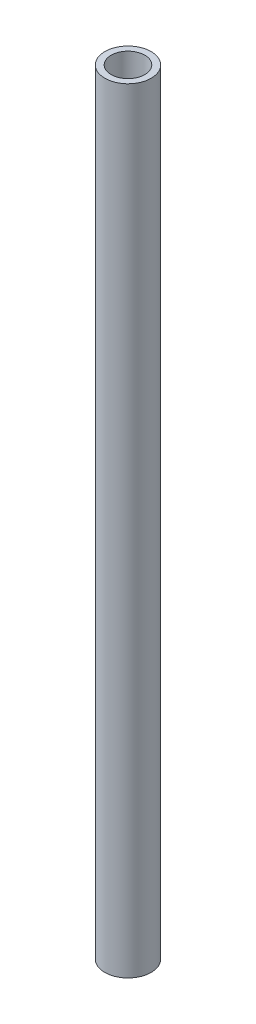
SolidWorks part; units mm, degrees
ref_plane "Front Plane" through (0, 0, 0) normal (0, 0, 1) x (1, 0, 0)
ref_plane "Top Plane" through (0, 0, 0) normal (0, 1, 0) x (1, 0, 0)
ref_plane "Right Plane" through (0, 0, 0) normal (1, 0, 0) x (0, 0, -1)
sketch "Sketch1" plane through (0, 0, 0) normal (0, 1, 0) x (1, 0, 0)
  circle A0 centre (0, 0) radius 12.1539
  circle A1 centre (0, 0) radius 16.7005
  dimension "D1" = 33.401
  dimension ".658" = 24.3078
extrude "Boss-Extrude1" add sketch "Sketch1" along normal mid plane 558.8
